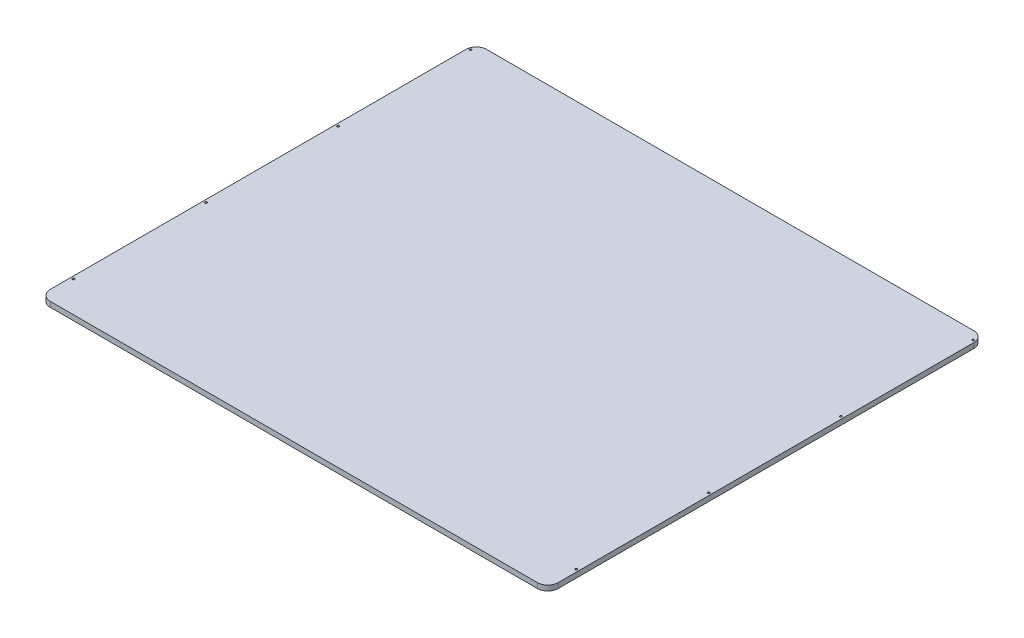
SolidWorks part; units mm, degrees
material "PMMA"
ref_plane "Front Plane" through (0, 0, 0) normal (0, 0, 1) x (1, 0, 0)
ref_plane "Top Plane" through (0, 0, 0) normal (0, 1, 0) x (1, 0, 0)
ref_plane "Right Plane" through (0, 0, 0) normal (1, 0, 0) x (0, 0, -1)
sketch "Sketch1" plane through (0, 0, 0) normal (0, 1, 0) x (1, 0, 0)
  line L1 (245, -210.5) -> (-245, -210.5)
  line L2 (245, -210.5) -> (245, 210.5)
  line L3 (245, 210.5) -> (-245, 210.5)
  line L4 (-245, -210.5) -> (-245, 210.5)
  line L5 (245, -210.5) -> (-245, 210.5) construction
  line L6 (245, 210.5) -> (-245, -210.5) construction
  point P0 (0, 0)
  dimension "D1" = 490
  dimension "D2" = 421
extrude "Boss-Extrude1" add sketch "Sketch1" along normal blind 5
sketch "Sketch2" plane through (0, 5, 0) normal (0, 1, 0) x (1, 0, 0)
  line L0 (-245, 210.5) -> (-245, -210.5) construction
  line L1 (-240, 180.5) -> (-235, 180.5)
  line L2 (-240, 180.5) -> (-240, 169.14)
  line L3 (-240, 169.14) -> (-235, 169.14)
  line L4 (-235, 180.5) -> (-235, 169.14)
  line L5 (245, 210.5) -> (-245, 210.5) construction
  dimension "D1" = 5
  dimension "D2" = 30
  dimension "D3" = 11.36
  dimension "D4" = 5
extrude "Cut-Extrude1" [suppressed] cut sketch "Sketch2" against normal through all
fillet "Fillet1" radius 10 4 edges at (245, 2.5, 210.5) (-245, 2.5, 210.5) (245, 2.5, -210.5) (-245, 2.5, -210.5)
pattern_linear "LPattern1" [suppressed] count 4 spacing 123.88
mirror "Mirror1" [suppressed] about plane through (0, 0, 0) normal (1, 0, 0)
hole_wizard "Tap Drill for M2.5x0.45 Tap1" positions "Sketch3" profile "Sketch4" hole size "M2.5x0.45" standard "ANSI Metric"
sketch "Sketch3" plane through (0, 0, 0) normal (0, -1, 0) x (-1, 0, 0)
  line L0 (235, -210.5) -> (-235, -210.5) construction
  line L1 (245, 200.5) -> (245, -200.5) construction
  point P0 (242.5, -180.5)
  dimension "D1" = 30
  dimension "D2" = 2.5
sketch "Sketch4" plane through (-242.5, 0, 180.5) normal (1, 0, 0) x (0, 0, -1)
  line L0 (0, 0) -> (0, 5.6159)
  line L1 (0, 5.6159) -> (1.025, 5)
  line L2 (1.025, 5) -> (1.025, 0)
  line L5 (1.025, 0) -> (0, 0)
  line L10 (0, 5.6159) -> (-1.025, 5) construction
  line L11 (0, -6.35) -> (0, 107.95) construction
  dimension "Hole Dia." = 2.05
  dimension "Hole Depth" = 5
  dimension "Drill Angle" = 118
pattern_linear "LPattern2" count 4 spacing 127.67 along (0, 0, -1) of "Tap Drill for M2.5x0.45 Tap1"
mirror "Mirror2" about plane through (0, 0, 0) normal (1, 0, 0) of "Tap Drill for M2.5x0.45 Tap1", "LPattern2"
